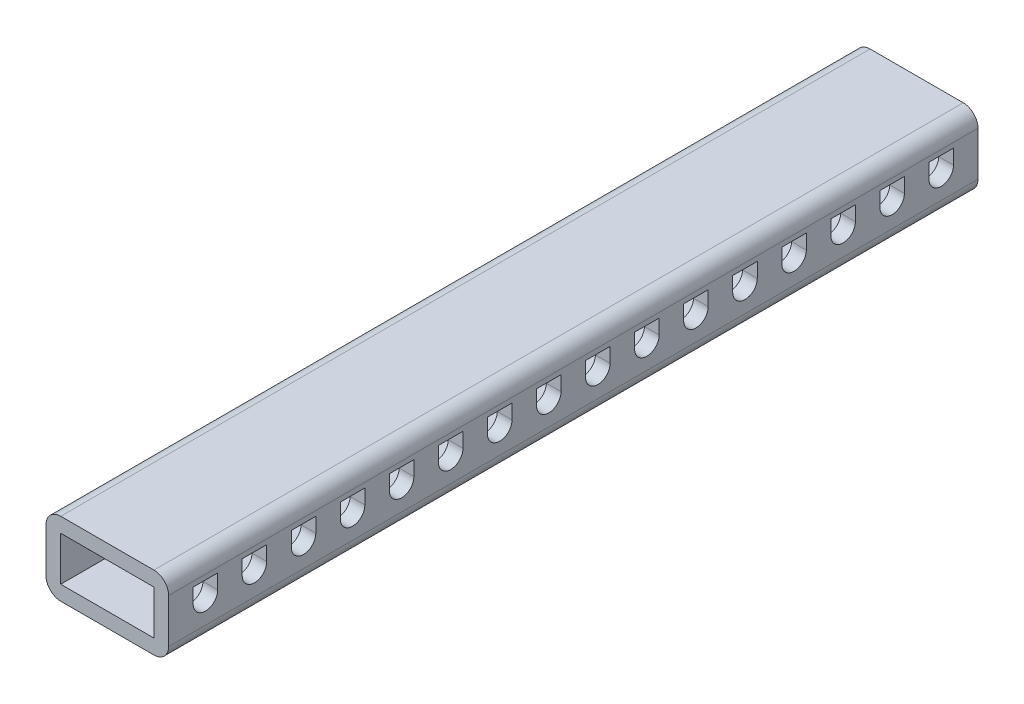
SolidWorks part; units mm, degrees
ref_plane "Front Plane" through (0, 0, 0) normal (0, 0, 1) x (1, 0, 0)
ref_plane "Top Plane" through (0, 0, 0) normal (0, 1, 0) x (1, 0, 0)
ref_plane "Right Plane" through (0, 0, 0) normal (1, 0, 0) x (0, 0, -1)
sketch "Sketch1" plane through (0, 0, 0) normal (0, 0, 1) x (1, 0, 0)
  line L1 (-12.5, 7.5) -> (12.5, 7.5)
  line L2 (-12.5, 7.5) -> (-12.5, -7.5)
  line L3 (-12.5, -7.5) -> (12.5, -7.5)
  line L4 (12.5, 7.5) -> (12.5, -7.5)
  line L5 (-12.5, 7.5) -> (12.5, -7.5) construction
  line L6 (-12.5, -7.5) -> (12.5, 7.5) construction
  point P0 (0, 0)
  dimension "D1" = 25
  dimension "D2" = 15
extrude "Boss-Extrude1" add sketch "Sketch1" along normal blind 190
sketch "Sketch2" plane through (0, 0, 190) normal (0, 0, 1) x (1, 0, 0)
  line L0 (-12.5, 7.5) -> (-12.5, -7.5) construction
  line L1 (-9.5, -4.5) -> (9.5, -4.5)
  line L2 (-9.5, -4.5) -> (-9.5, 4.5)
  line L3 (-9.5, 4.5) -> (9.5, 4.5)
  line L4 (9.5, -4.5) -> (9.5, 4.5)
  line L5 (-9.5, -4.5) -> (9.5, 4.5) construction
  line L6 (-9.5, 4.5) -> (9.5, -4.5) construction
  line L7 (12.5, 7.5) -> (-12.5, 7.5) construction
  point P0 (0, 0)
  dimension "D1" = 3
  dimension "D2" = 3
extrude "Cut-Extrude1" cut sketch "Sketch2" against normal blind 263
sketch "Sketch3" plane through (12.5, 0, 0) normal (1, 0, 0) x (0, 0, -1)
  line L1 (-190, 7.5) -> (0, 7.5) construction
  line L2 (-185, 3.5) -> (-180, 3.5)
  line L3 (-185, 3.5) -> (-185, 0.5)
  line L5 (-180, 3.5) -> (-180, 0.5)
  line L6 (-190, -7.5) -> (-190, 7.5) construction
  line L7 (-177.5, 7.5) -> (-177.5, 3.8883) construction
  line L8 (-175, 3.5) -> (-175, 0.5)
  line L9 (-170, 3.5) -> (-170, 0.5)
  line L10 (-170, 3.5) -> (-175, 3.5)
  line L11 (-167.5, 7.5) -> (-167.5, 3.8883) construction
  line L12 (-157.5, 7.5) -> (-157.5, 3.8883) construction
  line L13 (-165, 3.5) -> (-160, 3.5)
  line L14 (-165, 3.5) -> (-165, 0.5)
  line L15 (-160, 3.5) -> (-160, 0.5)
  line L16 (-155, 3.5) -> (-155, 0.5)
  line L17 (-150, 3.5) -> (-150, 0.5)
  line L18 (-150, 3.5) -> (-155, 3.5)
  line L19 (-147.5, 7.5) -> (-147.5, 3.8883) construction
  line L20 (-137.5, 7.5) -> (-137.5, 3.8883) construction
  line L21 (-155, 3.5) -> (-155, 0.5)
  line L22 (-150, 3.5) -> (-150, 0.5)
  line L23 (-150, 3.5) -> (-155, 3.5)
  line L24 (-145, 3.5) -> (-140, 3.5)
  line L25 (-145, 3.5) -> (-145, 0.5)
  line L26 (-140, 3.5) -> (-140, 0.5)
  line L27 (-135, 3.5) -> (-135, 0.5)
  line L28 (-130, 3.5) -> (-130, 0.5)
  line L29 (-130, 3.5) -> (-135, 3.5)
  line L30 (-127.5, 7.5) -> (-127.5, 3.8883) construction
  line L31 (-117.5, 7.5) -> (-117.5, 3.8883) construction
  line L32 (-107.5, 7.5) -> (-107.5, 3.8883) construction
  line L33 (-97.5, 7.5) -> (-97.5, 3.8883) construction
  line L34 (-135, 3.5) -> (-135, 0.5)
  line L35 (-130, 3.5) -> (-130, 0.5)
  line L36 (-130, 3.5) -> (-135, 3.5)
  line L37 (-125, 3.5) -> (-120, 3.5)
  line L38 (-125, 3.5) -> (-125, 0.5)
  line L39 (-120, 3.5) -> (-120, 0.5)
  line L40 (-125, 3.5) -> (-120, 3.5)
  line L41 (-125, 3.5) -> (-125, 0.5)
  line L42 (-120, 3.5) -> (-120, 0.5)
  line L43 (-115, 3.5) -> (-115, 0.5)
  line L44 (-110, 3.5) -> (-110, 0.5)
  line L45 (-110, 3.5) -> (-115, 3.5)
  line L46 (-105, 3.5) -> (-100, 3.5)
  line L47 (-105, 3.5) -> (-105, 0.5)
  line L48 (-100, 3.5) -> (-100, 0.5)
  line L49 (-95, 3.5) -> (-95, 0.5)
  line L50 (-90, 3.5) -> (-90, 0.5)
  line L51 (-90, 3.5) -> (-95, 3.5)
  line L52 (-87.5, 7.5) -> (-87.5, 3.8883) construction
  line L53 (-77.5, 7.5) -> (-77.5, 3.8883) construction
  line L54 (-67.5, 7.5) -> (-67.5, 3.8883) construction
  line L55 (-57.5, 7.5) -> (-57.5, 3.8883) construction
  line L56 (-47.5, 7.5) -> (-47.5, 3.8883) construction
  line L57 (-37.5, 7.5) -> (-37.5, 3.8883) construction
  line L58 (-27.5, 7.5) -> (-27.5, 3.8883) construction
  line L59 (-17.5, 7.5) -> (-17.5, 3.8883) construction
  line L60 (-95, 3.5) -> (-95, 0.5)
  line L61 (-90, 3.5) -> (-90, 0.5)
  line L62 (-90, 3.5) -> (-95, 3.5)
  line L63 (-85, 3.5) -> (-80, 3.5)
  line L64 (-85, 3.5) -> (-85, 0.5)
  line L65 (-80, 3.5) -> (-80, 0.5)
  line L66 (-75, 3.5) -> (-75, 0.5)
  line L67 (-70, 3.5) -> (-70, 0.5)
  line L68 (-70, 3.5) -> (-75, 3.5)
  line L69 (-75, 3.5) -> (-75, 0.5)
  line L70 (-70, 3.5) -> (-70, 0.5)
  line L71 (-70, 3.5) -> (-75, 3.5)
  line L72 (-65, 3.5) -> (-60, 3.5)
  line L73 (-65, 3.5) -> (-65, 0.5)
  line L74 (-60, 3.5) -> (-60, 0.5)
  line L75 (-65, 3.5) -> (-60, 3.5)
  line L76 (-65, 3.5) -> (-65, 0.5)
  line L77 (-60, 3.5) -> (-60, 0.5)
  line L78 (-55, 3.5) -> (-55, 0.5)
  line L79 (-50, 3.5) -> (-50, 0.5)
  line L80 (-50, 3.5) -> (-55, 3.5)
  line L81 (-45, 3.5) -> (-40, 3.5)
  line L82 (-45, 3.5) -> (-45, 0.5)
  line L83 (-40, 3.5) -> (-40, 0.5)
  line L84 (-45, 3.5) -> (-40, 3.5)
  line L85 (-45, 3.5) -> (-45, 0.5)
  line L86 (-40, 3.5) -> (-40, 0.5)
  line L87 (-35, 3.5) -> (-35, 0.5)
  line L88 (-30, 3.5) -> (-30, 0.5)
  line L89 (-30, 3.5) -> (-35, 3.5)
  line L90 (-25, 3.5) -> (-20, 3.5)
  line L91 (-25, 3.5) -> (-25, 0.5)
  line L92 (-20, 3.5) -> (-20, 0.5)
  line L93 (-15, 3.5) -> (-15, 0.5)
  line L94 (-10, 3.5) -> (-10, 0.5)
  line L95 (-10, 3.5) -> (-15, 3.5)
  line L96 (-15, 3.5) -> (-15, 0.5)
  line L97 (15, 3.5) -> (20, 3.5)
  line L98 (15, 3.5) -> (15, 0.5)
  line L99 (20, 3.5) -> (20, 0.5)
  line L100 (-7.5, 7.5) -> (-7.5, 3.8883) construction
  line L101 (2.5, 7.5) -> (2.5, 3.8883) construction
  line L102 (12.5, 7.5) -> (12.5, 3.8883) construction
  line L103 (-10, 3.5) -> (-10, 0.5)
  line L104 (-10, 3.5) -> (-15, 3.5)
  line L105 (-5, 3.5) -> (0, 3.5)
  line L106 (-5, 3.5) -> (-5, 0.5)
  line L107 (0, 3.5) -> (0, 0.5)
  line L108 (5, 3.5) -> (5, 0.5)
  line L109 (10, 3.5) -> (10, 0.5)
  line L110 (10, 3.5) -> (5, 3.5)
  line L111 (5, 3.5) -> (5, 0.5)
  line L112 (10, 3.5) -> (10, 0.5)
  line L113 (10, 3.5) -> (5, 3.5)
  line L114 (22.5, 7.5) -> (22.5, 3.8883) construction
  line L115 (15, 3.5) -> (20, 3.5)
  line L116 (15, 3.5) -> (15, 0.5)
  line L117 (20, 3.5) -> (20, 0.5)
  line L118 (15, 3.5) -> (20, 3.5)
  line L119 (15, 3.5) -> (15, 0.5)
  line L120 (20, 3.5) -> (20, 0.5)
  line L121 (25, 3.5) -> (25, 0.5)
  line L122 (30, 3.5) -> (30, 0.5)
  line L123 (30, 3.5) -> (25, 3.5)
  arc A0 (-185, 0.5) -> (-180, 0.5) centre (-182.5, 0.5) ccw
  arc A1 (-170, 0.5) -> (-175, 0.5) centre (-172.5, 0.5) cw
  arc A2 (-165, 0.5) -> (-160, 0.5) centre (-162.5, 0.5) ccw
  arc A3 (-150, 0.5) -> (-155, 0.5) centre (-152.5, 0.5) cw
  arc A4 (-150, 0.5) -> (-155, 0.5) centre (-152.5, 0.5) cw
  arc A5 (-145, 0.5) -> (-140, 0.5) centre (-142.5, 0.5) ccw
  arc A6 (-130, 0.5) -> (-135, 0.5) centre (-132.5, 0.5) cw
  arc A7 (-130, 0.5) -> (-135, 0.5) centre (-132.5, 0.5) cw
  arc A8 (-125, 0.5) -> (-120, 0.5) centre (-122.5, 0.5) ccw
  arc A9 (-125, 0.5) -> (-120, 0.5) centre (-122.5, 0.5) ccw
  arc A10 (-110, 0.5) -> (-115, 0.5) centre (-112.5, 0.5) cw
  arc A11 (-105, 0.5) -> (-100, 0.5) centre (-102.5, 0.5) ccw
  arc A12 (-90, 0.5) -> (-95, 0.5) centre (-92.5, 0.5) cw
  arc A13 (-90, 0.5) -> (-95, 0.5) centre (-92.5, 0.5) cw
  arc A14 (-85, 0.5) -> (-80, 0.5) centre (-82.5, 0.5) ccw
  arc A15 (-70, 0.5) -> (-75, 0.5) centre (-72.5, 0.5) cw
  arc A16 (-70, 0.5) -> (-75, 0.5) centre (-72.5, 0.5) cw
  arc A17 (-65, 0.5) -> (-60, 0.5) centre (-62.5, 0.5) ccw
  arc A18 (-65, 0.5) -> (-60, 0.5) centre (-62.5, 0.5) ccw
  arc A19 (-50, 0.5) -> (-55, 0.5) centre (-52.5, 0.5) cw
  arc A20 (-45, 0.5) -> (-40, 0.5) centre (-42.5, 0.5) ccw
  arc A21 (-45, 0.5) -> (-40, 0.5) centre (-42.5, 0.5) ccw
  arc A22 (-30, 0.5) -> (-35, 0.5) centre (-32.5, 0.5) cw
  arc A23 (-25, 0.5) -> (-20, 0.5) centre (-22.5, 0.5) ccw
  arc A24 (-10, 0.5) -> (-15, 0.5) centre (-12.5, 0.5) cw
  arc A25 (15, 0.5) -> (20, 0.5) centre (17.5, 0.5) ccw
  arc A26 (-10, 0.5) -> (-15, 0.5) centre (-12.5, 0.5) cw
  arc A27 (-5, 0.5) -> (0, 0.5) centre (-2.5, 0.5) ccw
  arc A28 (10, 0.5) -> (5, 0.5) centre (7.5, 0.5) cw
  arc A29 (10, 0.5) -> (5, 0.5) centre (7.5, 0.5) cw
  arc A30 (15, 0.5) -> (20, 0.5) centre (17.5, 0.5) ccw
  arc A31 (15, 0.5) -> (20, 0.5) centre (17.5, 0.5) ccw
  arc A32 (30, 0.5) -> (25, 0.5) centre (27.5, 0.5) cw
  point P18 (-170, 2)
  dimension "D1" = 4
  dimension "D2" = 5
  dimension "D3" = 5
  dimension "D4" = 3
  dimension "D5" = 5
  dimension "D6" = 5
extrude "Cut-Extrude2" cut sketch "Sketch3" against normal blind 263 contours L3 A0 L5 L2 | A1 L9 L10 L8 | L14 A2 L15 L13 | A3 L17 L18 L16 | L25 A5 L26 L24 | A6 L28 L29 L27 | L38 A8 L39 L37 | A10 L44 L45 L43 | L47 A11 L48 L46 | A12 L50 L51 L49 | L64 A14 L65 L63 | A15 L67 L68 L66 | L73 A17 L74 L72 | A19 L79 L80 L78 | L82 A20 L83 L81 | A22 L88 L89 L87 | L91 A23 L92 L90 | A24 L94 L95 L93 | L106 A27 L107 L105 | A28 L109 L110 L108 | L98 A25 L99 L97 | A32 L122 L123 L121
fillet "Fillet1" radius 3 4 edges at (-12.5, -7.5, 95) (12.5, -7.5, 95) (12.5, 7.5, 95) (-12.5, 7.5, 95)
sketch "Sketch4" plane through (0, 7.5, 0) normal (0, 1, 0) x (1, 0, 0)
  line L1 (-12.5, 0) -> (32.0756, 0)
  line L2 (-12.5, 0) -> (-12.5, -25)
  line L3 (-12.5, -25) -> (32.0756, -25)
  line L4 (32.0756, 0) -> (32.0756, -25)
  dimension "D1" = 25
extrude "Cut-Extrude3" cut sketch "Sketch4" against normal blind 35
